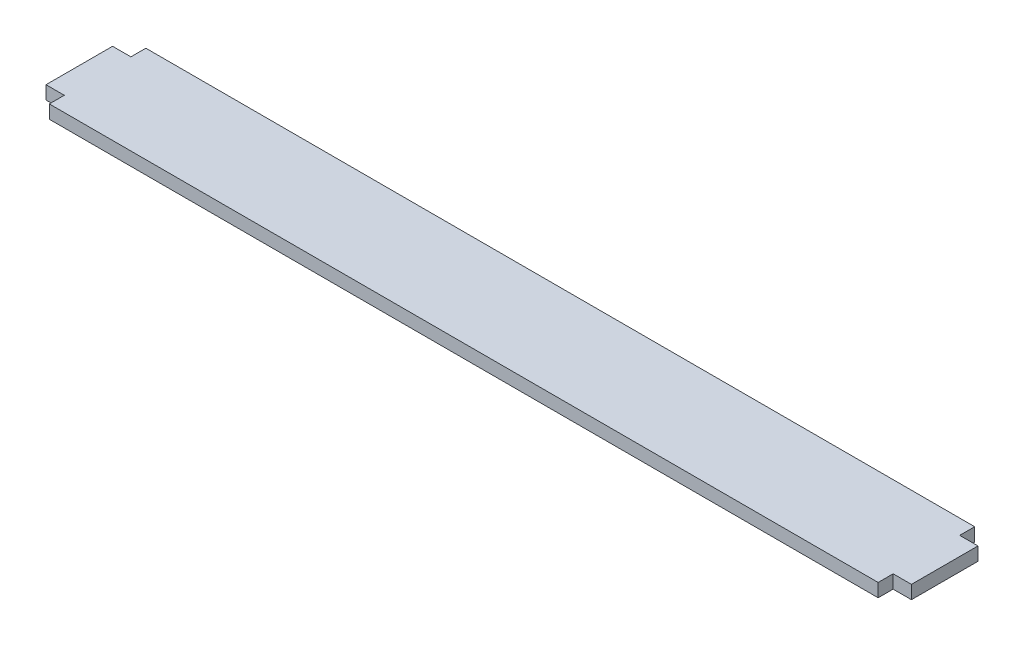
SolidWorks part; units mm, degrees
ref_plane "Спереди" through (0, 0, 0) normal (0, 0, 1) x (1, 0, 0)
ref_plane "Сверху" through (0, 0, 0) normal (0, 1, 0) x (1, 0, 0)
ref_plane "Справа" through (0, 0, 0) normal (1, 0, 0) x (0, 0, -1)
sketch "Эскиз1" plane through (0, 0, 0) normal (0, 1, 0) x (1, 0, 0)
  line L1 (-124.5, -14.4985) -> (124.5, -14.4985)
  line L2 (-124.5, -14.4985) -> (-124.5, 14.4985)
  line L3 (-124.5, 14.4985) -> (124.5, 14.4985)
  line L4 (124.5, -14.4985) -> (124.5, 14.4985)
  line L5 (-124.5, -14.4985) -> (124.5, 14.4985) construction
  line L6 (-124.5, 14.4985) -> (124.5, -14.4985) construction
  point P0 (0, 0)
  dimension "D1" = 28.997
  dimension "D2" = 249
extrude "Бобышка-Вытянуть1" add sketch "Эскиз1" along normal blind 4
sketch "Эскиз2" plane through (124.5, 0, 0) normal (1, 0, 0) x (0, 0, -1)
  line L0 (14.4985, 4) -> (-14.4985, 0) construction
  line L2 (-10, 4) -> (10, 4)
  line L3 (-10, 4) -> (-10, 0)
  line L4 (-10, 0) -> (10, 0)
  line L5 (10, 4) -> (10, 0)
  line L6 (-10, 4) -> (10, 0) construction
  line L7 (-10, 0) -> (10, 4) construction
  point P4 (0, 2)
  dimension "D1" = 4
  dimension "D2" = 20
extrude "Бобышка-Вытянуть2" add sketch "Эскиз2" along normal blind 5.5
mirror "Mirror1" about plane through (0, 0, 0) normal (1, 0, 0) of "Бобышка-Вытянуть2"
